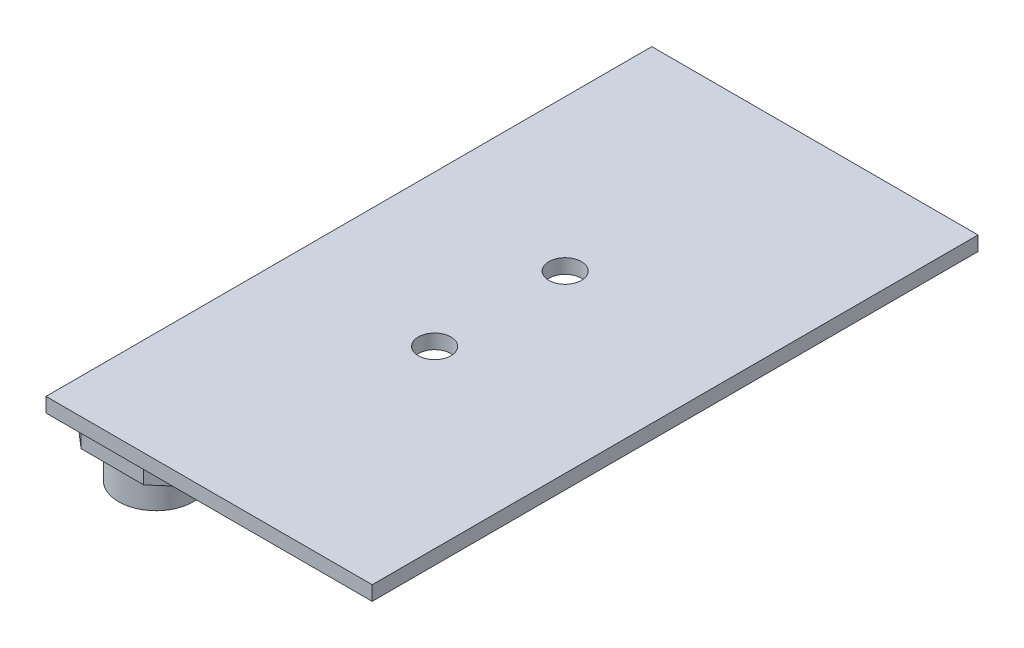
SolidWorks part; units mm, degrees
ref_plane "Front Plane" through (0, 0, 0) normal (0, 0, 1) x (1, 0, 0)
ref_plane "Top Plane" through (0, 0, 0) normal (0, 1, 0) x (1, 0, 0)
ref_plane "Right Plane" through (0, 0, 0) normal (1, 0, 0) x (0, 0, -1)
sketch "Sketch1" plane through (0, 0, 0) normal (0, 1, 0) x (1, 0, 0)
  line L1 (-20, 32.5) -> (15, 32.5)
  line L2 (-20, 32.5) -> (-20, -32.5)
  line L3 (-20, -32.5) -> (15, -32.5)
  line L4 (15, 32.5) -> (15, -32.5)
  point P4 (-20, 0)
  dimension "D1" = 65
  dimension "D2" = 35
  dimension "D3" = 15
extrude "Boss-Extrude1" add sketch "Sketch1" along normal mid plane 1.55
sketch "Sketch2" plane through (0, -0.775, 0) normal (0, -1, 0) x (1, 0, 0)
  line L0 (-3.8, 7) -> (-3.8, 4.17) construction
  line L1 (-5, 4.17) -> (-2.6, 4.17) construction
  line L2 (-14.508, 0) -> (9.5366, 0) construction
  circle A0 centre (-3.8, 7) radius 1.75
  circle A1 centre (-3.8, -7) radius 1.75
  dimension "D1" = 3.5
  dimension "D2" = 14
extrude "Cut-Extrude1" cut sketch "Sketch2" against normal through all
sketch "Sketch3" plane through (0, -0.775, 0) normal (0, -1, 0) x (1, 0, 0)
  line L0 (-20, 32.5) -> (15, 32.5) construction
  line L1 (-19.18, 19.33) -> (-11.78, 19.33)
  line L2 (-19.18, 19.33) -> (-19.18, 11.93)
  line L3 (-19.18, 11.93) -> (-11.78, 11.93)
  line L4 (-11.78, 19.33) -> (-11.78, 11.93)
  line L5 (-20, -32.5) -> (-20, 32.5) construction
  dimension "D1" = 7.4
  dimension "D2" = 20.57
  dimension "D3" = 0.82
extrude "Boss-Extrude2" add sketch "Sketch3" along normal blind 3.55 separate body
sketch "Sketch4" plane through (0, -0.775, 0) normal (0, -1, 0) x (1, 0, 0)
  line L0 (-20, -32.5) -> (-20, 32.5) construction
  line L1 (-19.53, 32.33) -> (-6.56, 32.33) construction
  line L2 (-19.53, 32.33) -> (-19.53, 22.97) construction
  line L3 (-19.53, 22.97) -> (-6.56, 22.97) construction
  line L4 (-6.56, 32.33) -> (-6.56, 22.97) construction
  line L5 (-20, 32.5) -> (15, 32.5) construction
  line L6 (-19.53, 29.62) -> (-19.53, 25.68)
  line L7 (-19.53, 27.65) -> (-6.56, 27.65) construction
  line L8 (-16.405, 32.33) -> (-9.685, 32.33)
  line L9 (-13.045, 32.33) -> (-13.045, 22.97) construction
  line L10 (-16.405, 32.33) -> (-19.53, 29.62)
  line L11 (-16.405, 22.97) -> (-9.685, 22.97)
  line L12 (-19.53, 25.68) -> (-16.405, 22.97)
  line L14 (-6.56, 25.68) -> (-9.685, 22.97)
  line L15 (-6.56, 29.62) -> (-6.56, 25.68)
  line L16 (-9.685, 32.33) -> (-6.56, 29.62)
  dimension "D1" = 12.97
  dimension "D2" = 9.36
  dimension "D3" = 0.47
  dimension "D4" = 0.17
  dimension "D5" = 3.94
  dimension "D6" = 6.72
extrude "Boss-Extrude3" add sketch "Sketch4" along normal blind 1.6 separate body
sketch "Sketch5" plane through (0, -2.375, 0) normal (0, -1, 0) x (1, 0, 0)
  line L0 (-19.53, 27.65) -> (-6.56, 27.65) construction
  circle A0 centre (-13.045, 27.65) radius 4
  dimension "D1" = 8
extrude "Boss-Extrude4" add sketch "Sketch5" along normal blind 3.6
